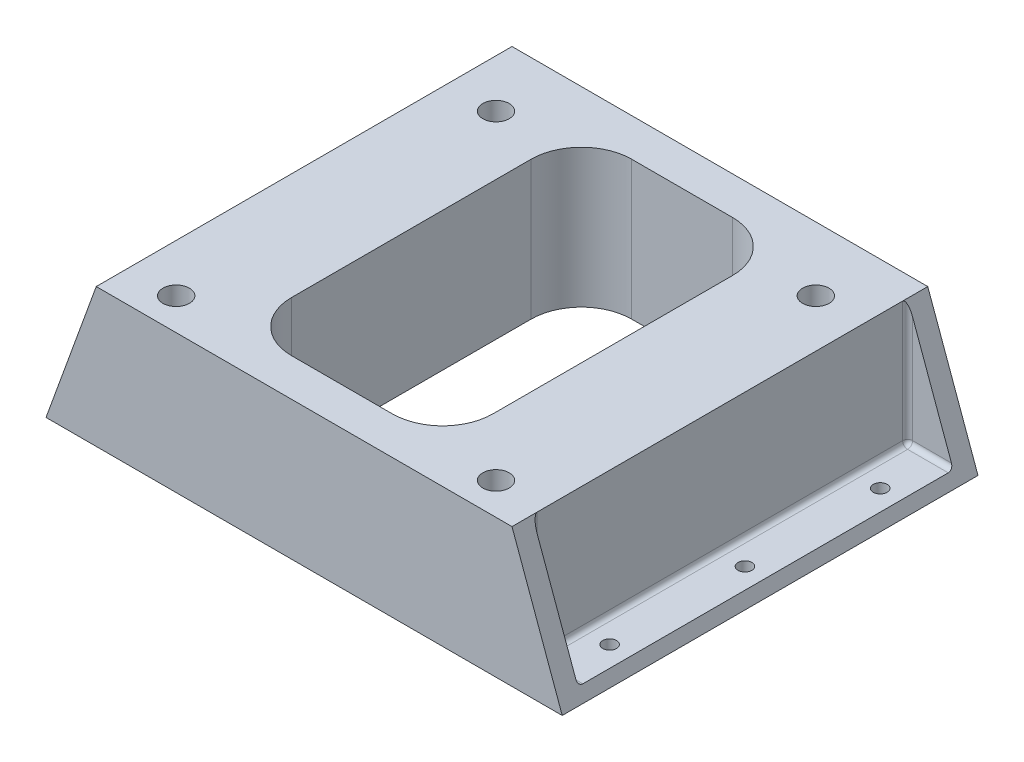
SolidWorks part; units mm, degrees
ref_plane "Front" through (0, 0, 0) normal (0, 0, 1) x (1, 0, 0)
ref_plane "Top" through (0, 0, 0) normal (0, 1, 0) x (1, 0, 0)
ref_plane "Right" through (0, 0, 0) normal (1, 0, 0) x (0, 0, -1)
sketch "Sketch1" plane through (0, 0, 0) normal (0, 1, 0) x (1, 0, 0)
  line L1 (-102.5, -82.55) -> (102.5, -82.55)
  line L2 (-102.5, -82.55) -> (-102.5, 82.55)
  line L3 (-102.5, 82.55) -> (102.5, 82.55)
  line L4 (102.5, -82.55) -> (102.5, 82.55)
  line L5 (-102.5, -82.55) -> (102.5, 82.55) construction
  line L6 (-102.5, 82.55) -> (102.5, -82.55) construction
  point P0 (0, 0)
  dimension "D1" = 165.1
  dimension "D2" = 205
extrude "Boss-Extrude1" add sketch "Sketch1" along normal blind 55
sketch "Sketch2" plane through (0, 0, 82.55) normal (0, 0, 1) x (1, 0, 0)
  line L0 (0, 55) -> (0, 0) construction
  line L1 (-102.5, 55) -> (102.5, 55) construction
  line L2 (0, 55) -> (82.55, 55) construction
  line L3 (0, 55) -> (-82.55, 55) construction
  line L4 (82.55, 55) -> (102.5, 0)
  line L5 (102.5, 55) -> (102.5, 0) construction
  line L6 (-82.55, 55) -> (-102.5, 0)
  line L7 (-102.5, 0) -> (-102.5, 55)
  line L8 (-102.5, 55) -> (-82.55, 55)
  line L9 (82.55, 55) -> (102.5, 55)
  line L10 (102.5, 55) -> (102.5, 0)
  dimension "D1" = 165.1
extrude "Cut-Extrude1" cut sketch "Sketch2" against normal up to next
sketch "Sketch3" plane through (0, 55, 0) normal (0, 1, 0) x (1, 0, 0)
  line L0 (-82.55, 82.55) -> (-82.55, -82.55) construction
  line L1 (-82.55, 74.55) -> (-102.5, 74.55)
  line L2 (-82.55, 74.55) -> (-82.55, -74.55)
  line L3 (-82.55, -74.55) -> (-102.5, -74.55)
  line L4 (-102.5, 74.55) -> (-102.5, -74.55)
  line L5 (-82.55, 74.55) -> (-102.5, -74.55) construction
  line L6 (-82.55, -74.55) -> (-102.5, 74.55) construction
  line L7 (-102.5, 82.55) -> (-102.5, -82.55) construction
  line L8 (82.55, 82.55) -> (82.55, -82.55) construction
  line L9 (82.55, 74.55) -> (102.5, 74.55)
  line L10 (82.55, 74.55) -> (82.55, -74.55)
  line L11 (82.55, -74.55) -> (102.5, -74.55)
  line L12 (102.5, 74.55) -> (102.5, -74.55)
  line L13 (82.55, 74.55) -> (102.5, -74.55) construction
  line L14 (82.55, -74.55) -> (102.5, 74.55) construction
  line L15 (102.5, -82.55) -> (102.5, 82.55) construction
  line L16 (-82.55, 82.55) -> (-102.5, 82.55) construction
  line L17 (-102.5, -82.55) -> (-82.55, -82.55) construction
  point P4 (-92.525, 0)
  point P13 (92.525, 0)
  dimension "D1" = 8
  dimension "D2" = 8
extrude "Cut-Extrude2" cut sketch "Sketch3" against normal offset from surface (50 mm away) 5 up to face at (0, 0, 0)
sketch "Sketch4" plane through (0, 5, 0) normal (0, 1, 0) x (1, 0, 0)
  line L0 (-92.5, 74.55) -> (-92.5, -74.55) construction
  line L1 (-100.6864, 74.55) -> (-82.55, 74.55) construction
  line L2 (-100.6864, -74.55) -> (-82.55, -74.55) construction
  line L3 (0, 82.55) -> (0, 0) construction
  line L4 (82.55, 82.55) -> (-82.55, 82.55) construction
  line L5 (0, 0) -> (-102.5, 0) construction
  line L6 (-102.5, 82.55) -> (-102.5, -82.55) construction
  circle A0 centre (-92.5, 53.7115) radius 2.75
  circle A1 centre (-92.5, 0) radius 2.75
  circle A2 centre (-92.5, -53.7115) radius 2.75
  circle A3 centre (92.5, -53.7115) radius 2.75
  circle A4 centre (92.5, 0) radius 2.75
  circle A5 centre (92.5, 53.7115) radius 2.75
  dimension "D2" = 5.5
  dimension "D1" = 10
extrude "Cut-Extrude3" cut sketch "Sketch4" against normal up to next
fillet "Fillet1" radius 2 10 edges at (91.6182, 5, 74.55) (82.55, 30, 74.55) (82.55, 5, 0) (91.6182, 5, -74.55) (82.55, 30, -74.55) (-82.55, 30, 74.55) (-91.6182, 5, 74.55) (-82.55, 30, -74.55) (-82.55, 5, 0) (-91.6182, 5, -74.55)
sketch "Sketch5" plane through (0, 55, 0) normal (0, 1, 0) x (1, 0, 0)
  line L0 (63.5, -65.659) -> (63.5, -74.041) construction
  line L1 (50.8, -65.659) -> (76.2, -65.659) construction
  line L2 (76.2, -74.041) -> (50.8, -74.041) construction
  line L3 (63.5, 61.341) -> (63.5, 52.959) construction
  line L4 (50.8, 61.341) -> (76.2, 61.341) construction
  line L5 (76.2, 52.959) -> (50.8, 52.959) construction
  circle A0 centre (63.5, -69.85) radius 5.25
  circle A1 centre (63.5, 57.15) radius 5.25
  dimension "D1" = 10.5
extrude "Cut-Extrude4" cut sketch "Sketch5" against normal blind 10
mirror "Mirror1" about plane through (0, 0, 0) normal (1, 0, 0) of "Cut-Extrude4"
sketch "Sketch6" plane through (0, 55, 0) normal (0, 1, 0) x (1, 0, 0)
  line L0 (0, 82.55) -> (0, -82.55) construction
  line L1 (82.55, 82.55) -> (-82.55, 82.55) construction
  line L2 (-82.55, -82.55) -> (82.55, -82.55) construction
  line L4 (-40, -67.55) -> (40, -67.55)
  line L5 (-40, -67.55) -> (-40, 67.55)
  line L6 (-40, 67.55) -> (40, 67.55)
  line L7 (40, -67.55) -> (40, 67.55)
  line L8 (-40, -67.55) -> (40, 67.55) construction
  line L9 (-40, 67.55) -> (40, -67.55) construction
  point P6 (0, 0)
  dimension "D1" = 15
  dimension "D2" = 80
extrude "Cut-Extrude5" cut sketch "Sketch6" against normal up to next
fillet "Fillet2" radius 20 4 edges at (-40, 27.5, 67.55) (40, 27.5, 67.55) (40, 27.5, -67.55) (-40, 27.5, -67.55)
